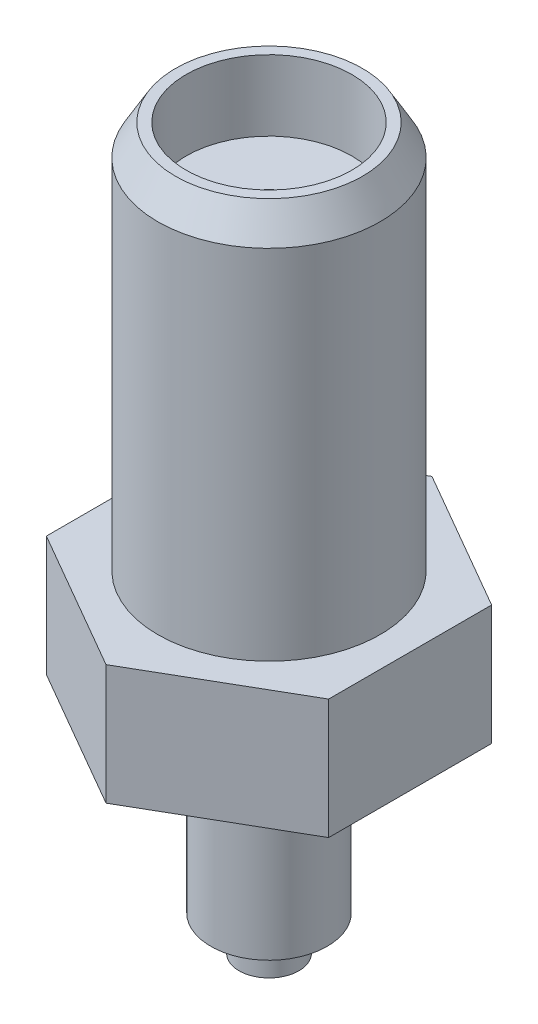
SolidWorks part; units mm, degrees
material "Латунь"
ref_plane "Спереди" through (0, 0, 0) normal (0, 0, 1) x (1, 0, 0)
ref_plane "Сверху" through (0, 0, 0) normal (0, 1, 0) x (1, 0, 0)
ref_plane "Справа" through (0, 0, 0) normal (1, 0, 0) x (0, 0, -1)
sketch "Эскиз1" plane through (0, 0, 0) normal (0, 0, 1) x (1, 0, 0)
  line L0 (2.35, 11) -> (2.35, 9)
  line L1 (2.35, 11) -> (3.15, 11)
  line L2 (2.35, 9) -> (0.5, 9)
  line L4 (3.15, 11) -> (3.15, 0)
  line L5 (0.5, 9) -> (0.5, 4)
  line L6 (1.65, -3.4) -> (5, -3.4)
  line L7 (5, -3.4) -> (5, 0)
  line L8 (5, 0) -> (3.15, 0)
  line L9 (0.5, 4) -> (0, 4)
  line L10 (0.85, -8.4) -> (1.65, -8.4)
  line L11 (1.65, -8.4) -> (1.65, -3.4)
  line L12 (0, 0) -> (0, 50000) construction
  line L13 (0, -9.4) -> (0.85, -9.4)
  line L14 (0.85, -9.4) -> (0.85, -8.4)
  line L15 (0, 4) -> (0, -9.4)
  dimension "D1" = 6.3
  dimension "D2" = 4.7
  dimension "D3" = 1
  dimension "D4" = 10
  dimension "D5" = 3.3
  dimension "D6" = 1.7
  dimension "D7" = 11
  dimension "D8" = 2
  dimension "D9" = 5
  dimension "D10" = 3.4
  dimension "D11" = 5
  dimension "D12" = 1
revolve "Повернуть1" add sketch "Эскиз1" angle 360 about L12
chamfer "Фаска1" distance 0.5 angle 60 1 edges at (0, 11, -3.15)
sketch "Эскиз2" plane through (0, 0, 0) normal (0, 1, 0) x (1, 0, 0)
  line L0 (-4, 2.3094) -> (-4, -2.3094)
  line L1 (-4, -2.3094) -> (0, -4.6188)
  line L2 (0, -4.6188) -> (4, -2.3094)
  line L3 (4, -2.3094) -> (4, 2.3094)
  line L4 (4, 2.3094) -> (0, 4.6188)
  line L5 (0, 4.6188) -> (-4, 2.3094)
  circle A0 centre (0, 0) radius 4 construction
  circle A1 centre (0, 0) radius 5
  circle A2 centre (0, 0) radius 5 construction
  dimension "D1" = 8
extrude "Вырез-Вытянуть1" cut sketch "Эскиз2" against normal up to next
